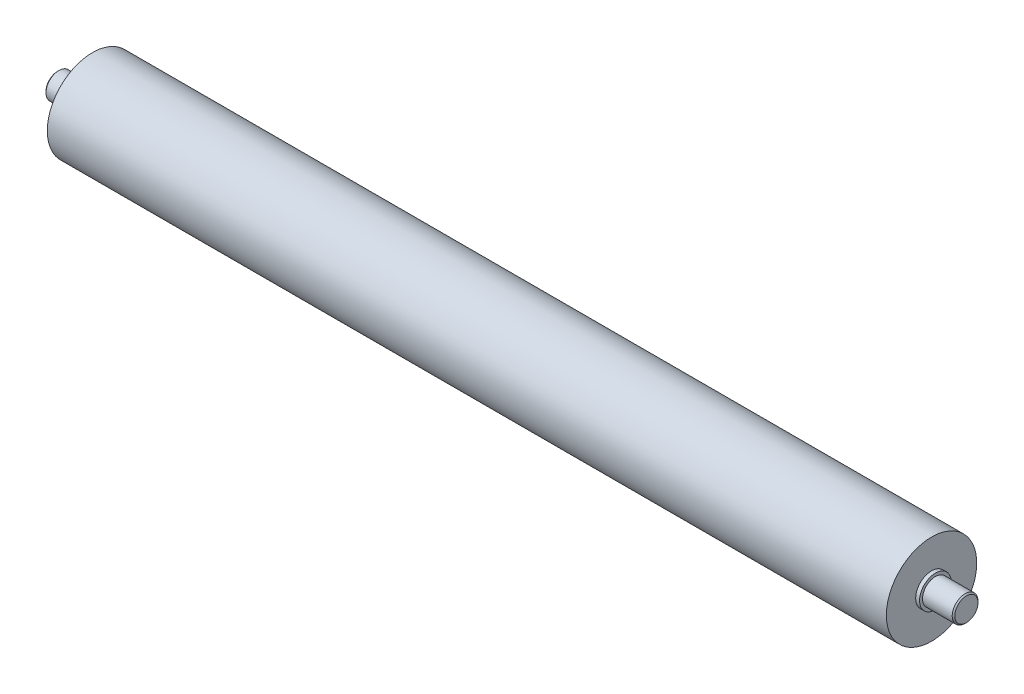
SolidWorks part; units mm, degrees
material "灰铸铁"
ref_plane "前视基准面" through (0, 0, 0) normal (0, 0, 1) x (1, 0, 0)
ref_plane "上视基准面" through (0, 0, 0) normal (0, 1, 0) x (1, 0, 0)
ref_plane "右视基准面" through (0, 0, 0) normal (1, 0, 0) x (0, 0, -1)
sketch "草图1" plane through (0, 0, 0) normal (0, 1, 0) x (1, 0, 0)
  line L0 (-176, 0) -> (176, 0)
  line L4 (176, 0) -> (176, 5)
  line L7 (162.5, 17.5) -> (-162.5, 17.5)
  line L10 (-176, 5) -> (-176, 0)
  line L11 (-176, 5) -> (-164, 5)
  line L12 (-164, 5) -> (-164, 6.15)
  line L13 (-164, 6.15) -> (-162.5, 6.15)
  line L14 (-162.5, 6.15) -> (-162.5, 17.5)
  line L15 (176, 5) -> (164, 5)
  line L16 (164, 5) -> (164, 6.15)
  line L17 (164, 6.15) -> (162.5, 6.15)
  line L18 (162.5, 6.15) -> (162.5, 17.5)
  point P4 (0, 0)
  dimension "D1" = 352
  dimension "D2" = 5
  dimension "D3" = 5
  dimension "D4" = 1.5
  dimension "D5" = 1.5
  dimension "D6" = 17.5
  dimension "D7" = 12
  dimension "D8" = 12
  dimension "D9" = 1.15
  dimension "D10" = 1.15
revolve "旋转1" add sketch "草图1" angle 360 about L0
chamfer "倒角1" distance 0.5 angle 45 2 edges at (176, 0, 5) (-176, 0, 5)
